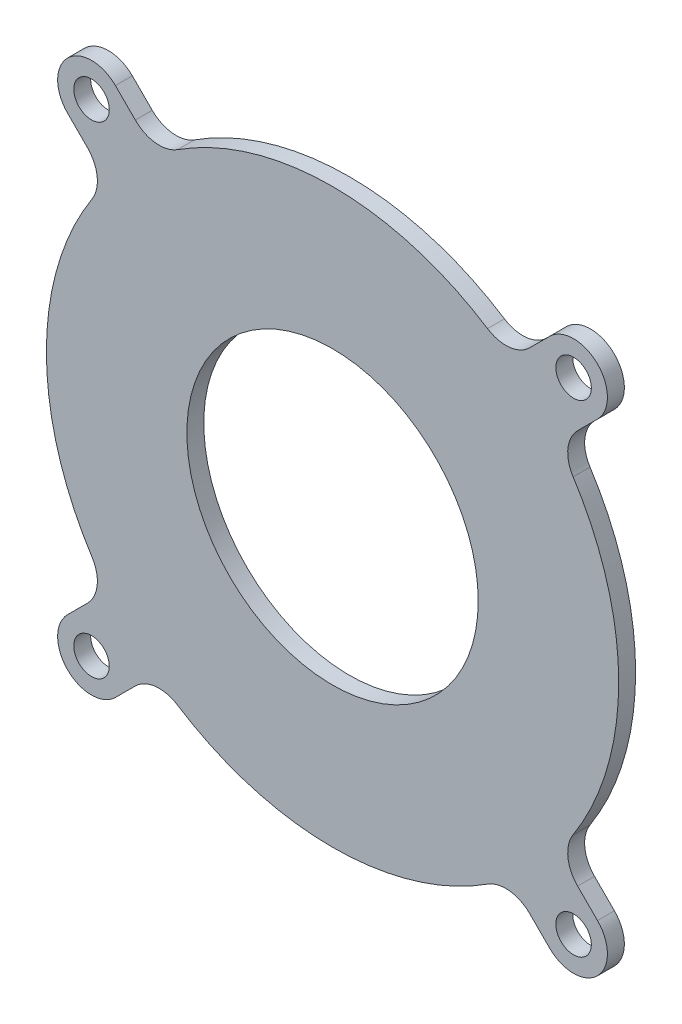
SolidWorks part; units mm, degrees
ref_plane "前视基准面" through (0, 0, 0) normal (0, 0, 1) x (1, 0, 0)
ref_plane "上视基准面" through (0, 0, 0) normal (0, 1, 0) x (1, 0, 0)
ref_plane "右视基准面" through (0, 0, 0) normal (1, 0, 0) x (0, 0, -1)
sketch "草图1" plane through (0, 0, 0) normal (0, 0, 1) x (1, 0, 0)
  line L0 (0, 0) -> (47.1, 0) construction
  line L2 (0, 0) -> (47.1, -47.1) construction
  line L3 (47.1, -47.1) -> (52.0497, -52.0497) construction
  line L6 (54.05, 6.95) -> (-6.95, 6.95) construction
  line L8 (23.55, -23.55) -> (23.55, -16.6688) construction
  line L14 (52.0497, -52.0497) -> (48.0497, -56.0497) construction
  line L23 (-1.2931, 6.95) -> (48.3931, 6.95) construction
  line L27 (49.2213, -54.8782) -> (46.8701, -52.5269)
  line L28 (54.8782, -49.2213) -> (52.5269, -46.8701)
  line L29 (-2.1213, -54.8782) -> (0.2299, -52.5269)
  line L47 (-7.7782, -49.2213) -> (-5.4269, -46.8701)
  line L48 (-7.7782, 2.1213) -> (-5.4269, -0.2299)
  line L49 (23.55, -23.55) -> (41.8752, 4.8928) construction
  line L53 (-2.1213, 7.7782) -> (0.2299, 5.4269)
  line L60 (49.2213, 7.7782) -> (46.8701, 5.4269)
  line L61 (54.8782, 2.1213) -> (52.5269, -0.2299)
  circle A15 centre (52.0497, -52.0497) radius 2.1
  circle A16 centre (52.0497, -52.0497) radius 4 construction
  arc A17 (49.2213, -54.8782) -> (54.8782, -49.2213) centre (52.0497, -52.0497) ccw
  arc A18 (-7.7782, -49.2213) -> (-2.1213, -54.8782) centre (-4.9497, -52.0497) ccw
  arc A19 (-2.1213, 7.7782) -> (-7.7782, 2.1213) centre (-4.9497, 4.9497) ccw
  arc A20 (54.8782, 2.1213) -> (49.2213, 7.7782) centre (52.0497, 4.9497) ccw
  circle A25 centre (-4.9497, -52.0497) radius 2.1
  circle A26 centre (-4.9497, 4.9497) radius 2.1
  circle A27 centre (52.0497, 4.9497) radius 2.1
  circle A31 centre (23.55, -23.55) radius 33.835 construction
  arc A32 (5.2248, -51.9928) -> (41.8752, -51.9928) centre (23.55, -23.55) ccw
  arc A33 (51.9928, -41.8752) -> (51.9928, -5.2248) centre (23.55, -23.55) ccw
  arc A34 (5.2248, 4.8928) -> (41.8752, 4.8928) centre (23.55, -23.55) cw
  arc A35 (-4.8928, -5.2248) -> (-4.8928, -41.8752) centre (23.55, -23.55) ccw
  arc A36 (-4.8928, -5.2248) -> (-5.4269, -0.2299) centre (-8.2553, -3.0584) ccw
  arc A37 (0.2299, 5.4269) -> (5.2248, 4.8928) centre (3.0584, 8.2553) ccw
  arc A38 (41.8752, 4.8928) -> (46.8701, 5.4269) centre (44.0416, 8.2553) ccw
  arc A39 (52.5269, -0.2299) -> (51.9928, -5.2248) centre (55.3553, -3.0584) ccw
  arc A40 (51.9928, -41.8752) -> (52.5269, -46.8701) centre (55.3553, -44.0416) ccw
  arc A41 (46.8701, -52.5269) -> (41.8752, -51.9928) centre (44.0416, -55.3553) ccw
  arc A42 (5.2248, -51.9928) -> (0.2299, -52.5269) centre (3.0584, -55.3553) ccw
  arc A43 (-5.4269, -46.8701) -> (-4.8928, -41.8752) centre (-8.2553, -44.0416) ccw
  circle A49 centre (23.55, -23.55) radius 17.225
  point P67 (50.1356, -44.4788)
  point P70 (44.4788, -50.1356)
  dimension "D2" = 4
  dimension "D3" = 34.45
  dimension "D8" = 4
  dimension "D5" = 4
  dimension "D1" = 47.1
  dimension "D11" = 4
extrude "凸台-拉伸1" add sketch "草图1" along normal blind 2
